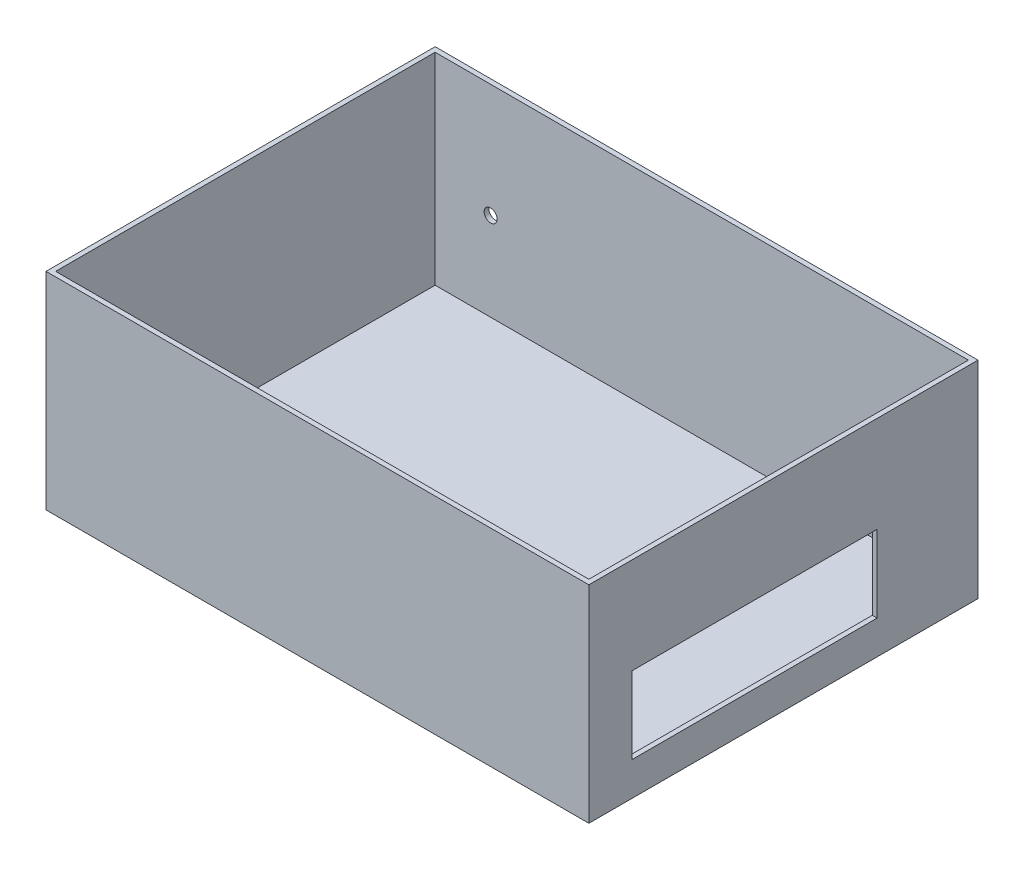
SolidWorks part; units mm, degrees
ref_plane "Front Plane" through (0, 0, 0) normal (0, 0, 1) x (1, 0, 0)
ref_plane "Top Plane" through (0, 0, 0) normal (0, 1, 0) x (1, 0, 0)
ref_plane "Right Plane" through (0, 0, 0) normal (1, 0, 0) x (0, 0, -1)
sketch "Sketch1" plane through (0, 0, 0) normal (0, 1, 0) x (1, 0, 0)
  line L1 (-56.5, -40.5) -> (56.5, -40.5)
  line L2 (-56.5, -40.5) -> (-56.5, 40.5)
  line L3 (-56.5, 40.5) -> (56.5, 40.5)
  line L4 (56.5, -40.5) -> (56.5, 40.5)
  line L5 (-56.5, -40.5) -> (56.5, 40.5) construction
  line L6 (-56.5, 40.5) -> (56.5, -40.5) construction
  point P0 (0, 0)
  dimension "BoxLength" = 113
  dimension "BoxWidth" = 81
extrude "Boss-Extrude1" add sketch "Sketch1" along normal blind 1
sketch "Sketch2" plane through (0, 1, 0) normal (0, 1, 0) x (1, 0, 0)
  line L1 (-56.5, -40.5) -> (56.5, -40.5)
  line L2 (-56.5, -40.5) -> (-56.5, 40.5)
  line L3 (-56.5, 40.5) -> (56.5, 40.5)
  line L4 (56.5, -40.5) -> (56.5, 40.5)
  line L5 (-56.5, -40.5) -> (56.5, 40.5) construction
  line L6 (-56.5, 40.5) -> (56.5, -40.5) construction
  line L7 (-55.5, -39.5) -> (55.5, -39.5)
  line L8 (-55.5, -39.5) -> (-55.5, 39.5)
  line L9 (-55.5, 39.5) -> (55.5, 39.5)
  line L10 (55.5, -39.5) -> (55.5, 39.5)
  line L11 (-55.5, -39.5) -> (55.5, 39.5) construction
  line L12 (-55.5, 39.5) -> (55.5, -39.5) construction
  point P0 (0, 0)
  point P7 (0, 0)
  point P12 (0, 0)
  dimension "D1" = 1
  dimension "D2" = 1
extrude "Boss-Extrude3" add sketch "Sketch2" along normal blind 42
sketch "Sketch3" plane through (56.5, 0, 0) normal (1, 0, 0) x (0, 0, -1)
  line L0 (-40.5, 0) -> (40.5, 0) construction
  line L1 (-31.5, 7) -> (19.5, 7)
  line L2 (-31.5, 7) -> (-31.5, 23)
  line L3 (-31.5, 23) -> (19.5, 23)
  line L4 (19.5, 7) -> (19.5, 23)
  line L5 (-31.5, 7) -> (19.5, 23) construction
  line L6 (-31.5, 23) -> (19.5, 7) construction
  line L7 (-40.5, 43) -> (-40.5, 0) construction
  point P0 (-6, 15)
  dimension "D1" = 7
  dimension "D2" = 9
  dimension "D3" = 51
  dimension "D4" = 16
extrude "Cut-Extrude2" cut sketch "Sketch3" against normal up to next
sketch "Sketch4" plane through (0, 1, 0) normal (0, 1, 0) x (1, 0, 0)
  line L0 (55.5, 39.5) -> (-55.5, 39.5) construction
  line L1 (-55.5, -39.5) -> (55.5, -39.5) construction
  line L2 (55.5, -39.5) -> (55.5, 39.5) construction
  line L5 (-55.5, 39.5) -> (-55.5, -39.5) construction
  circle A0 centre (52.05, 34.25) radius 1.55
  circle A1 centre (-52.05, -35.5) radius 1.55
  circle A2 centre (52.05, 34.25) radius 0.55
  circle A3 centre (-52.05, -35.5) radius 0.55
  dimension "D2" = 2.45
  dimension "D3" = 3.1
  dimension "D4" = 3.1
  dimension "D6" = 5
  dimension "D7" = 1
  dimension "D8" = 1
  dimension "D1" = 3.7
  dimension "D5" = 5
extrude "Boss-Extrude4" add sketch "Sketch4" along normal blind 1.1
sketch "Sketch6" plane through (0, 0, -40.5) normal (0, 0, -1) x (-1, 0, 0)
  line L0 (56.5, 43) -> (56.5, 0) construction
  line L2 (-56.5, 43) -> (-56.5, 0) construction
  line L3 (-56.5, 43) -> (56.5, 43) construction
  circle A0 centre (-46.35, 24.55) radius 1.35
  circle A1 centre (43.95, 19.35) radius 1.35
  dimension "D1" = 2.7
  dimension "D3" = 8.8
  dimension "D4" = 17.1
  dimension "D2" = 11.2
  dimension "D5" = 22.3
extrude "Cut-Extrude3" cut sketch "Sketch6" against normal up to next
equation "\"BoxLength\"= 113"
equation "\"BoxWidth\"= 81"
equation "\"BoxLength@Sketch1\"=\"BoxLength\""
equation "\"BoxWidth@Sketch1\"=\"BoxWidth\""
